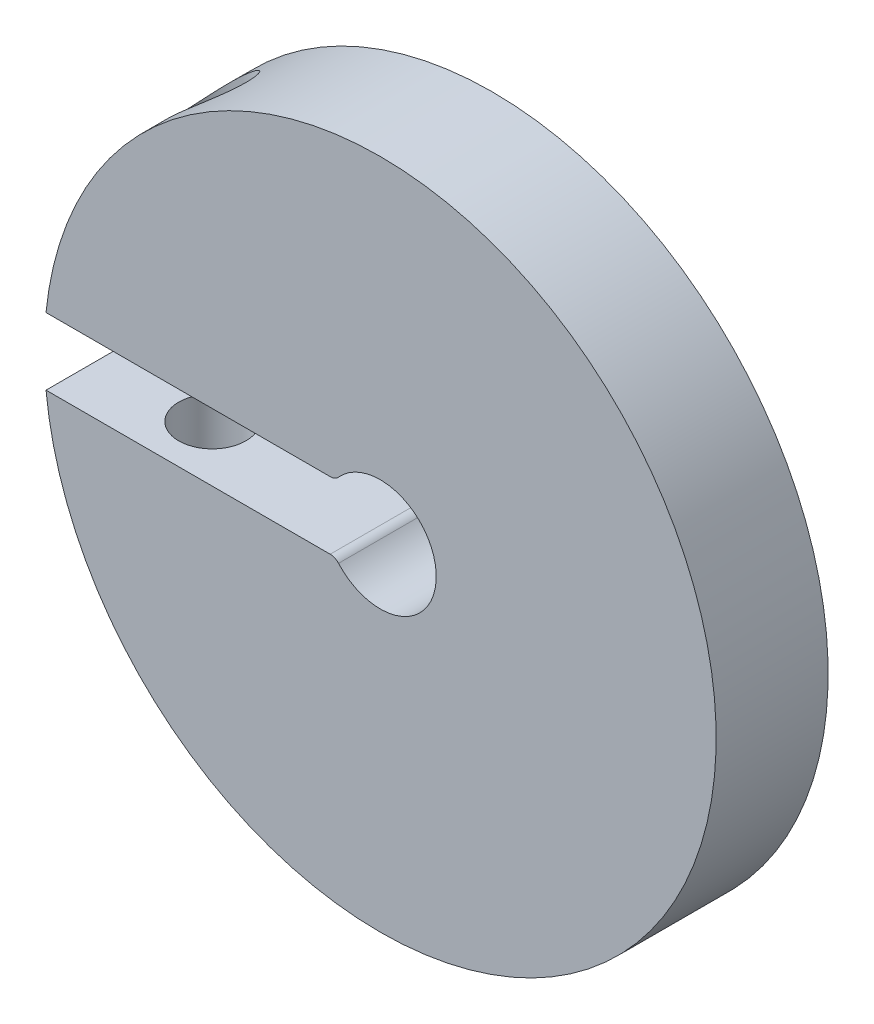
SolidWorks part; units mm, degrees
ref_plane "Plan de face" through (0, 0, 0) normal (0, 0, 1) x (1, 0, 0)
ref_plane "Plan de dessus" through (0, 0, 0) normal (0, 1, 0) x (1, 0, 0)
ref_plane "Plan de droite" through (0, 0, 0) normal (1, 0, 0) x (0, 0, -1)
sketch "Esquisse1" plane through (0, 0, 0) normal (0, 0, 1) x (1, 0, 0)
  circle A0 centre (0, 0) radius 2.5
  circle A1 centre (0, 0) radius 15
  dimension "D1" = 5
  dimension "D2" = 30
extrude "Boss.-Extru.1" add sketch "Esquisse1" along normal blind 5
sketch "Esquisse2" plane through (0, 0, 0) normal (0, 1, 0) x (1, 0, 0)
  line L1 (-23.0864, -2.5) -> (28.4499, -2.5) construction
  line L2 (-15, 0) -> (-15, -5) construction
  line L3 (15, 0) -> (-15, 0) construction
  circle A1 centre (-10, -2.5) radius 1.5
  dimension "D1" = 5
  dimension "D3" = 3
  dimension "D2" = 2.5
extrude "Enlèv. mat.-Extru.1" cut sketch "Esquisse2" against normal through all and the other way through all
sketch "Esquisse3" plane through (0, 0, 5) normal (0, 0, 1) x (1, 0, 0)
  line L0 (-32.6562, 0) -> (2.5, 0) construction
  line L1 (-14.9248, 1.5) -> (-2.5, 1.5)
  line L3 (-2.5, -1.5) -> (-14.9248, -1.5)
  line L4 (-2.5, 1.5) -> (-2, 1.5)
  line L5 (-2.5, -1.5) -> (-2, -1.5)
  circle A0 centre (0, 0) radius 15 construction
  arc A1 (-14.9248, 1.5) -> (-14.9248, -1.5) centre (0, 0) ccw
  arc A4 (-2, 1.5) -> (-2, -1.5) centre (0, 0) ccw
  dimension "D2" = 3
extrude "Enlèv. mat.-Extru.3" cut sketch "Esquisse3" against normal blind 10
fillet "Congé2" radius 0.5 2 edges at (-2, -1.5, 2.5) (-2, 1.5, 2.5)
